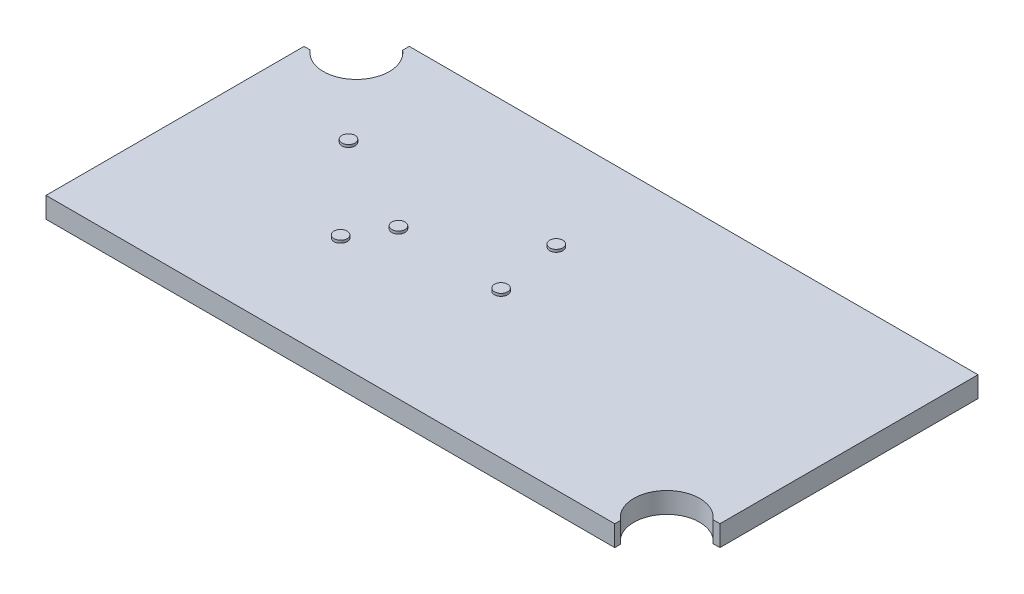
SolidWorks part; units mm, degrees
ref_plane "Front" through (0, 0, 0) normal (0, 0, 1) x (1, 0, 0)
ref_plane "Top" through (0, 0, 0) normal (0, 1, 0) x (1, 0, 0)
ref_plane "Right" through (0, 0, 0) normal (1, 0, 0) x (0, 0, -1)
sketch "Sketch1" plane through (0, 0, 0) normal (0, 1, 0) x (1, 0, 0)
  line L0 (-15, -7.5) -> (15, 7.5) construction
  line L1 (-12.46, 7.5) -> (15, 7.5)
  line L3 (-15, -7.5) -> (12.46, -7.5)
  line L4 (15, 7.5) -> (15, -4.96)
  line L5 (12.46, -7.5) -> (12.46, -7.2186)
  line L6 (14.6678, -4.96) -> (15, -4.96)
  line L7 (-12.46, 7.5) -> (-12.46, 7.1818)
  line L8 (-15, 4.96) -> (-14.7073, 4.96)
  line L9 (-15, 4.96) -> (-15, -7.5)
  arc A0 (-14.7073, 4.96) -> (-12.46, 7.1818) centre (-13.476, 5.962) ccw
  arc A1 (14.6678, -4.96) -> (12.46, -7.2186) centre (13.448, -5.976) ccw
  point P4 (0, 0)
  dimension "D3" = 3.175
  dimension "D2" = 15
  dimension "D4" = 13.462
  dimension "D5" = 30
  dimension "D6" = 1.524
  dimension "D7" = 1.524
  dimension "D8" = 2.54
  dimension "D9" = 2.54
  dimension "D10" = 2.54
  dimension "D11" = 2.54
  dimension "D12" = 28.448
extrude "Boss-Extrude1" add sketch "Sketch1" along normal blind 1
sketch "Sketch2" plane through (0, 1, 0) normal (0, 1, 0) x (1, 0, 0)
  line L0 (-15, 4.96) -> (-15, -7.5) construction
  line L1 (-15, -7.5) -> (12.46, -7.5) construction
  circle A0 centre (-9.92, 2.025) radius 0.3175
  circle A1 centre (-5.094, -0.388) radius 0.3175
  circle A2 centre (-6.11, -2.166) radius 0.3175
  circle A3 centre (-0.522, 2.66) radius 0.3175
  circle A4 centre (-0.014, -0.515) radius 0.3175
  dimension "D1" = 0.635
  dimension "D8" = 10.16
  dimension "D9" = 14.478
  dimension "D10" = 6.985
  dimension "D11" = 14.986
  dimension "D2" = 5.08
  dimension "D3" = 9.525
  dimension "D4" = 8.89
  dimension "D5" = 5.334
  dimension "D6" = 9.906
  dimension "D7" = 7.112
extrude "Boss-Extrude2" add sketch "Sketch2" along normal blind 0.127
